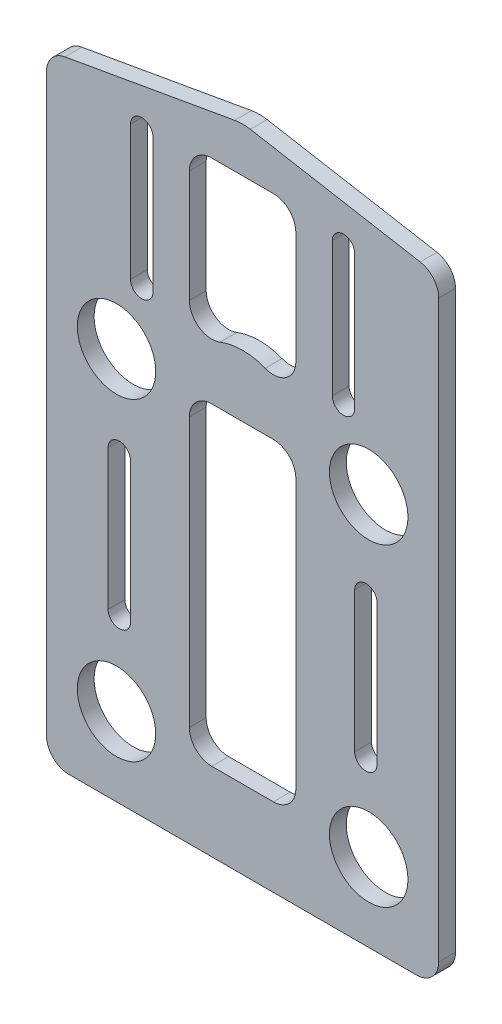
SolidWorks part; units mm, degrees
ref_plane "Front Plane" through (0, 0, 0) normal (0, 0, 1) x (1, 0, 0)
ref_plane "Top Plane" through (0, 0, 0) normal (0, 1, 0) x (1, 0, 0)
ref_plane "Right Plane" through (0, 0, 0) normal (1, 0, 0) x (0, 0, -1)
sketch "Sketch1" plane through (0, 0, 0) normal (0, 0, 1) x (1, 0, 0)
  line L0 (4.75, 24.512) -> (4.75, 14.512)
  line L1 (-4.75, 14.512) -> (-4.75, 24.512)
  line L2 (-2.75, 26.512) -> (2.75, 26.512)
  line L3 (-0.6946, 30.4512) -> (-15.8473, 27.7794)
  line L4 (-17.5, 25.8098) -> (-17.5, -25.488)
  line L5 (-15.5, -27.488) -> (15.5, -27.488)
  line L6 (17.5, -25.488) -> (17.5, 25.8098)
  line L7 (15.8473, 27.7794) -> (0.6946, 30.4512)
  line L8 (2.75, -20.488) -> (-2.75, -20.488)
  line L9 (-4.75, -18.488) -> (-4.75, 5.512)
  line L10 (-2.75, 7.512) -> (2.75, 7.512)
  line L11 (4.75, 5.512) -> (4.75, -18.488)
  line L12 (-12, -12.988) -> (-12, -0.488)
  line L13 (-10, -0.488) -> (-10, -12.988)
  line L14 (-10, 13.512) -> (-10, 25.512)
  line L15 (-8, 25.512) -> (-8, 13.512)
  line L16 (10, -12.988) -> (10, -0.488)
  line L17 (12, -0.488) -> (12, -12.988)
  line L18 (8, 13.512) -> (8, 25.512)
  line L19 (10, 25.512) -> (10, 13.512)
  arc A0 (4.75, 14.512) -> (2.0177, 12.6509) centre (2.75, 14.512) cw
  arc A1 (2.0177, 12.6509) -> (-2.0177, 12.6509) centre (0, 7.5228) ccw
  arc A2 (-2.0177, 12.6509) -> (-4.75, 14.512) centre (-2.75, 14.512) cw
  arc A3 (-4.75, 24.512) -> (-2.75, 26.512) centre (-2.75, 24.512) cw
  arc A4 (2.75, 26.512) -> (4.75, 24.512) centre (2.75, 24.512) cw
  arc A5 (-15.8473, 27.7794) -> (-17.5, 25.8098) centre (-15.5, 25.8098) ccw
  arc A6 (-17.5, -25.488) -> (-15.5, -27.488) centre (-15.5, -25.488) ccw
  arc A7 (15.5, -27.488) -> (17.5, -25.488) centre (15.5, -25.488) ccw
  arc A8 (17.5, 25.8098) -> (15.8473, 27.7794) centre (15.5, 25.8098) ccw
  arc A9 (0.6946, 30.4512) -> (-0.6946, 30.4512) centre (0, 26.512) ccw
  arc A10 (-2.75, -20.488) -> (-4.75, -18.488) centre (-2.75, -18.488) cw
  arc A11 (-4.75, 5.512) -> (-2.75, 7.512) centre (-2.75, 5.512) cw
  arc A12 (2.75, 7.512) -> (4.75, 5.512) centre (2.75, 5.512) cw
  arc A13 (4.75, -18.488) -> (2.75, -20.488) centre (2.75, -18.488) cw
  circle A14 centre (-11.25, 7.512) radius 3.5
  circle A15 centre (-11.25, -20.488) radius 3.5
  circle A16 centre (11.25, -20.488) radius 3.5
  circle A17 centre (11.25, 7.512) radius 3.5
  arc A18 (-10, -12.988) -> (-12, -12.988) centre (-11, -12.988) cw
  arc A19 (-12, -0.488) -> (-10, -0.488) centre (-11, -0.488) cw
  arc A20 (-8, 13.512) -> (-10, 13.512) centre (-9, 13.512) cw
  arc A21 (-10, 25.512) -> (-8, 25.512) centre (-9, 25.512) cw
  arc A22 (12, -12.988) -> (10, -12.988) centre (11, -12.988) cw
  arc A23 (10, -0.488) -> (12, -0.488) centre (11, -0.488) cw
  arc A24 (10, 13.512) -> (8, 13.512) centre (9, 13.512) cw
  arc A25 (8, 25.512) -> (10, 25.512) centre (9, 25.512) cw
extrude "camera-plate" add sketch "Sketch1" against normal blind 1.5
